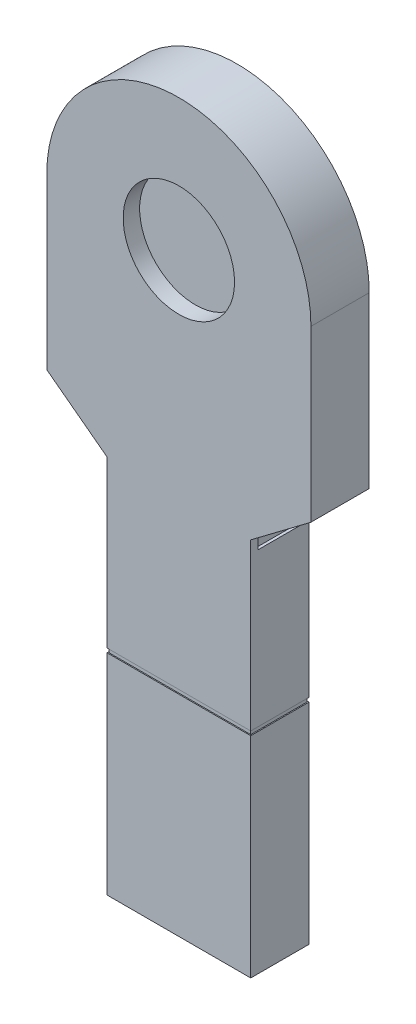
SolidWorks part; units mm, degrees
ref_plane "Спереди" through (0, 0, 0) normal (0, 0, 1) x (1, 0, 0)
ref_plane "Сверху" through (0, 0, 0) normal (0, 1, 0) x (1, 0, 0)
ref_plane "Справа" through (0, 0, 0) normal (1, 0, 0) x (0, 0, -1)
sketch "Эскиз1" plane through (0, 0, 0) normal (0, 0, 1) x (1, 0, 0)
  line L0 (-102, 0) -> (-102, -131)
  line L1 (-102, -131) -> (-55.5, -166.0403)
  line L2 (-55.5, -166.0403) -> (-55.5, -459.0403)
  line L3 (-55.5, -459.0403) -> (55.5, -459.0403)
  line L4 (55.5, -459.0403) -> (55.5, -166.0403)
  line L5 (102, 0) -> (102, -131)
  line L6 (102, -131) -> (55.5, -166.0403)
  arc A0 (102, 0) -> (-102, 0) centre (0, 0) ccw
  dimension "D1" = 204
  dimension "D2" = 131
  dimension "D3" = 127
  dimension "D4" = 111
  dimension "D5" = 58.2243
  dimension "D6" = 293
extrude "Бобышка-Вытянуть1" add sketch "Эскиз1" along normal blind 45
sketch "Эскиз2" plane through (0, 0, 45) normal (0, 0, 1) x (1, 0, 0)
  circle A0 centre (0, 0) radius 43
  dimension "D1" = 86
extrude "Вырез-Вытянуть1" cut sketch "Эскиз2" against normal blind 12.7
sketch3d "Трехмерный эскиз1"
  line L0 (55.5, -166.0403, 39.25) -> (55.5, -166.0403, 5.75) construction
  line L1 (55.5, -166.0403, 45) -> (55.5, -166.0403, 0) construction
  line L2 (55.5, -166.0403, 5.75) -> (91.8573, -138.6431, 5.75) construction
  line L3 (91.8573, -138.6431, 5.75) -> (91.8573, -138.6431, 39.25) construction
  line L4 (91.8573, -138.6431, 39.25) -> (55.5, -166.0403, 39.25)
  line L5 (55.5, -166.0403, 39.25) -> (55.5, -175.4906, 39.25)
  line L6 (55.5, -175.4906, 39.25) -> (55.5, -175.4906, 5.75) construction
  line L7 (55.5, -175.4906, 5.75) -> (55.5, -166.0403, 5.75) construction
  line L8 (55.5, -166.0403, 45) -> (102, -131, 45) construction
  line L9 (55.5, -459.0403, 45) -> (55.5, -166.0403, 45) construction
  line L10 (55.5, -175.4906, 39.25) -> (53.3162, -175.4906, 39.25)
  line L11 (53.3162, -175.4906, 39.25) -> (53.3162, -155.7906, 39.25)
  line L12 (53.3162, -155.7906, 39.25) -> (86.1401, -131.056, 39.25)
  line L13 (86.1401, -131.056, 39.25) -> (91.8573, -138.6431, 39.25)
  line L14 (86.1401, -131.056, 39.25) -> (86.1401, -131.056, 5.75) construction
  line L15 (86.1401, -131.056, 5.75) -> (91.8573, -138.6431, 5.75) construction
  line L16 (86.1401, -131.056, 5.75) -> (53.3162, -155.7906, 5.75) construction
  line L17 (53.3162, -155.7906, 5.75) -> (53.3162, -155.7906, 39.25) construction
  line L18 (53.3162, -155.7906, 5.75) -> (55.5, -166.0403, 5.75) construction
  line L19 (53.3162, -155.7906, 5.75) -> (53.3162, -175.4906, 5.75) construction
  line L20 (53.3162, -175.4906, 5.75) -> (55.5, -175.4906, 5.75) construction
  line L21 (53.3162, -175.4906, 5.75) -> (53.3162, -175.4906, 39.25) construction
  line L22 (55.5, -166.0403, 0) -> (102, -131, 0) construction
  line L23 (55.5, -459.0403, 0) -> (55.5, -166.0403, 0) construction
  line L24 (55.5, -166.0403, 39.25) -> (53.3162, -155.7906, 39.25) construction
  line L26 (102, -131, 45) -> (102, -131, 0) construction
  point P22 (55.5, -166.0403, 22.5)
  point P23 (55.5, -166.0403, 22.5)
  dimension "D1" = 12.7
  dimension "D2" = 9.5
  dimension "D3" = 33.5
  dimension "D4" = 41.1
  dimension "D5" = 19.7
extrude "Вырез-Вытянуть6" cut sketch "Трехмерный эскиз1" along direction (0, 0, 1) on the side of the normal blind 33.5 contours L12 L13 L4 L5 L10 L11
mirror "Зеркальное отражение1" about plane through (0, 0, 0) normal (1, 0, 0) of "Вырез-Вытянуть6"
sketch "Эскиз6" plane through (0, 0, 45) normal (0, 0, 1) x (1, 0, 0)
  line L0 (55.5, -293.8403) -> (54.7, -293.8403)
  line L1 (55.5, -459.0403) -> (55.5, -166.0403) construction
  line L2 (54.7, -293.8403) -> (54.7, -297.0403)
  line L3 (54.7, -297.0403) -> (55.5, -297.0403)
  line L4 (55.5, -297.0403) -> (55.5, -293.8403)
  dimension "D1" = 162
  dimension "D2" = 3.2
  dimension "D3" = 0.8
sketch3d "Трехмерный эскиз2"
  line L0 (55.5, -295.4403, 45) -> (55.5, -295.4403, 0)
  line L1 (55.5, -297.0403, 45) -> (55.5, -293.8403, 45) construction
  line L3 (55.5, -295.4403, 0) -> (-55.5, -295.4403, 0)
  line L4 (-55.5, -166.0403, 0) -> (-55.5, -459.0403, 0) construction
  line L5 (-55.5, -295.4403, 0) -> (-55.5, -295.4403, 45)
  line L6 (-55.5, -166.0403, 45) -> (-55.5, -459.0403, 45) construction
  line L7 (-55.5, -295.4403, 45) -> (55.5, -295.4403, 45)
  line L8 (55.5, -459.0403, 45) -> (55.5, -459.0403, 0) construction
  line L9 (-55.5, -459.0403, 0) -> (55.5, -459.0403, 0) construction
  line L10 (-55.5, -459.0403, 45) -> (-55.5, -459.0403, 0) construction
sweep "Вырез-По траектории1" cut profiles "Эскиз6" path "Трехмерный эскиз2"
